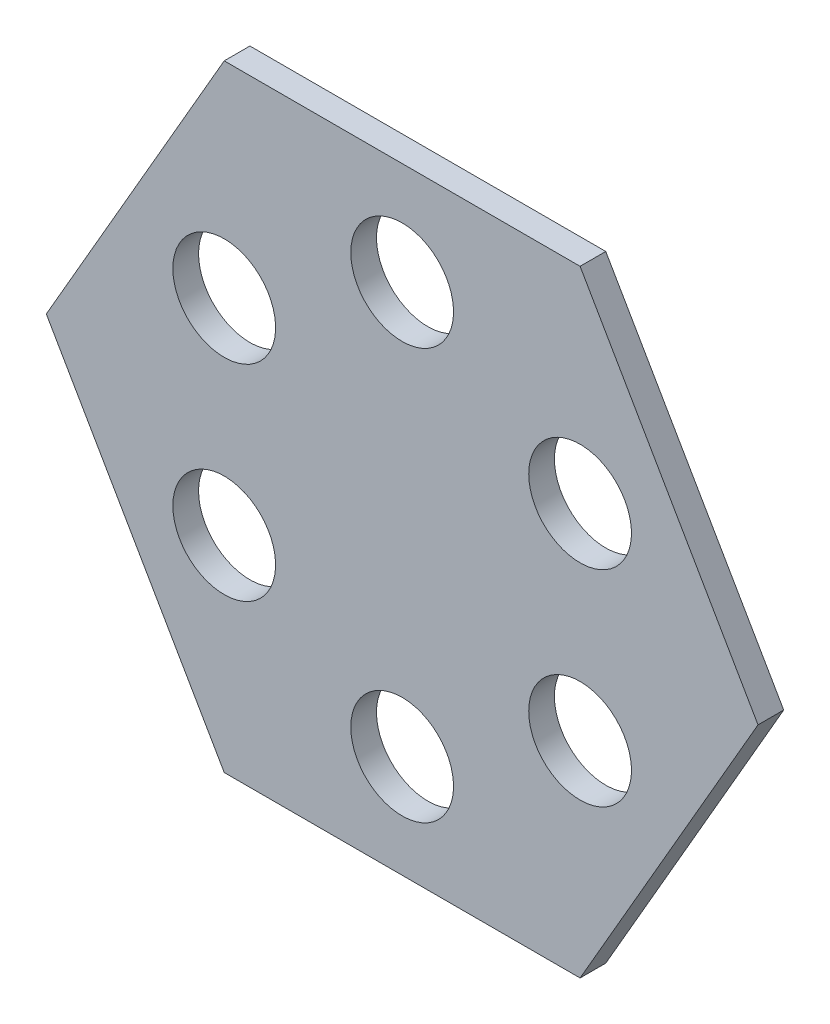
SolidWorks part; units mm, degrees
ref_plane "Front Plane" through (0, 0, 0) normal (0, 0, 1) x (1, 0, 0)
ref_plane "Top Plane" through (0, 0, 0) normal (0, 1, 0) x (1, 0, 0)
ref_plane "Right Plane" through (0, 0, 0) normal (1, 0, 0) x (0, 0, -1)
sketch "Sketch1" plane through (0, 0, 0) normal (0, 0, 1) x (1, 0, 0)
  line L0 (0, 0) -> (-131.9823, 228.6)
  line L1 (-131.9823, 228.6) -> (131.9823, 228.6)
  line L2 (131.9823, 228.6) -> (0, 0)
  line L3 (0, 0) -> (131.9823, 228.6)
  line L4 (131.9823, 228.6) -> (263.9645, 0)
  line L5 (263.9645, 0) -> (0, 0)
  line L6 (0, 0) -> (263.9645, 0)
  line L7 (263.9645, 0) -> (131.9823, -228.6)
  line L8 (131.9823, -228.6) -> (0, 0)
  line L9 (0, 0) -> (131.9823, -228.6)
  line L10 (131.9823, -228.6) -> (-131.9823, -228.6)
  line L11 (-131.9823, -228.6) -> (0, 0)
  line L12 (0, 0) -> (-131.9823, -228.6)
  line L13 (-131.9823, -228.6) -> (-263.9645, 0)
  line L14 (-263.9645, 0) -> (0, 0)
  line L15 (0, 0) -> (-263.9645, 0)
  line L16 (-263.9645, 0) -> (-131.9823, 228.6)
  line L17 (-131.9823, 228.6) -> (0, 0)
  circle A0 centre (0, 152.4) radius 38.1
  circle A1 centre (131.9823, 76.2) radius 38.1
  circle A2 centre (131.9823, -76.2) radius 38.1
  circle A3 centre (0, -152.4) radius 38.1
  circle A4 centre (-131.9823, -76.2) radius 38.1
  circle A5 centre (-131.9823, 76.2) radius 38.1
  point P29 (0, 0)
  dimension "D2" = 76.2
  dimension "D1" = 60
  dimension "D3" = 228.6
  dimension "D4" = 152.4
  dimension "D5" = 6
extrude "Boss-Extrude1" add sketch "Sketch1" along normal blind 19.05 contours L16 L14 L0 A5 | L2 L1 L0 A0 | L5 L4 L2 A1 | L8 L7 L5 A2 | L11 L10 L8 A3 | L14 L13 L11 A4
